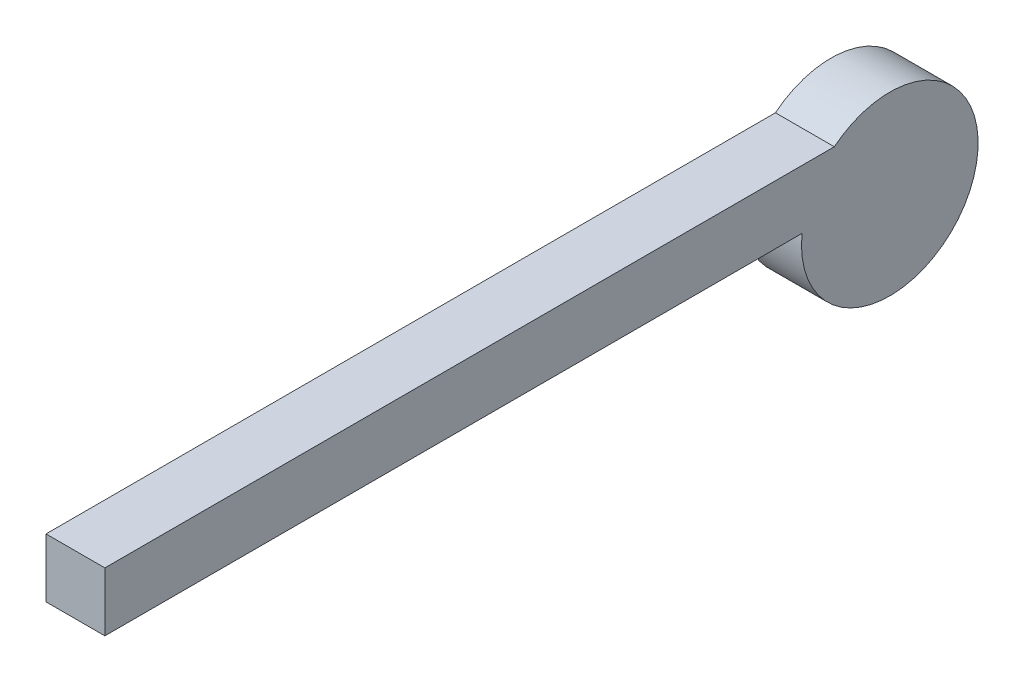
SolidWorks part; units mm, degrees
ref_plane "Front Plane" through (0, 0, 0) normal (0, 0, 1) x (1, 0, 0)
ref_plane "Top Plane" through (0, 0, 0) normal (0, 1, 0) x (1, 0, 0)
ref_plane "Right Plane" through (0, 0, 0) normal (1, 0, 0) x (0, 0, -1)
sketch "Sketch1" plane through (0, 0, 0) normal (1, 0, 0) x (0, 0, -1)
  line L1 (0, 5) -> (-400, 5)
  line L2 (0, 5) -> (0, 35)
  line L3 (0, 35) -> (-400, 35)
  line L4 (-400, 5) -> (-400, 35)
  circle A0 centre (0, 0) radius 45
  dimension "D1" = 90
  dimension "D2" = 30
  dimension "D3" = 400
  dimension "D4" = 5
extrude "Boss-Extrude1" add sketch "Sketch1" along normal mid plane 30 contours L3 A0 L1 L2 | A0 L3 L4 L1 | L1 A0 L3 L2
